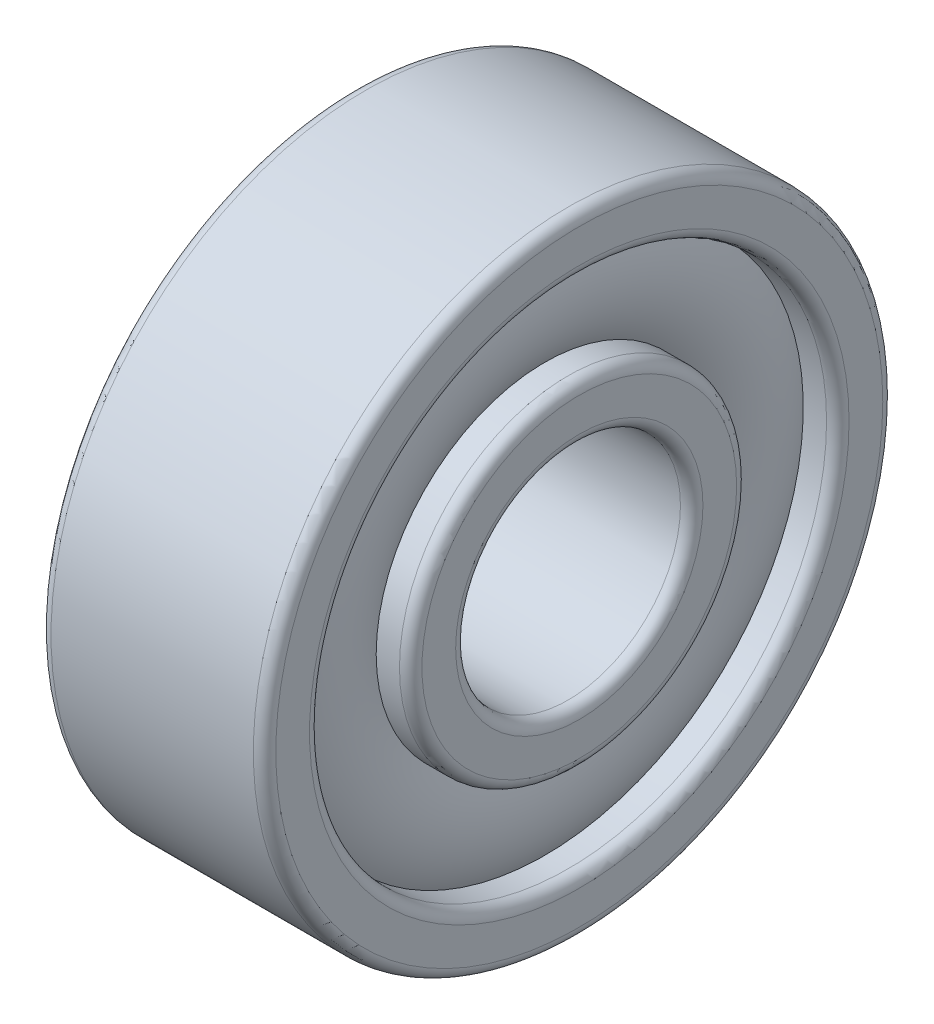
SolidWorks part; units mm, degrees
ref_plane "前视基准面" through (0, 0, 0) normal (0, 0, 1) x (1, 0, 0)
ref_plane "上视基准面" through (0, 0, 0) normal (0, 1, 0) x (1, 0, 0)
ref_plane "右视基准面" through (0, 0, 0) normal (1, 0, 0) x (0, 0, -1)
other "Configuration Table"
sketch "草图1" plane through (0, 0, 0) normal (0, 0, 1) x (1, 0, 0)
  line L0 (-5.5784, 0) -> (6.3176, 0)
  line L2 (2.5, 2.5) -> (2.5, 3.75)
  line L3 (2.5, 7) -> (-2.5, 7)
  line L4 (-2.5, 2.5) -> (-2.5, 3.75)
  line L5 (2.5, 2.5) -> (-2.5, 7) construction
  line L6 (2.5, 7) -> (-2.5, 2.5) construction
  line L7 (-2.5, 2.5) -> (-2.5, 0)
  line L8 (2.5, 2.5) -> (2.5, 0)
  line L9 (-2.5, 0) -> (2.5, 0)
  line L10 (-2.5, 7) -> (-2.5, 5.75)
  line L11 (2.5, 7) -> (2.5, 5.75)
  line L12 (2.5, 5.75) -> (1.7321, 5.75)
  line L13 (2.5, 5.75) -> (2.5, 7)
  line L14 (-2.5, 3.75) -> (-1.7321, 3.75)
  line L15 (-1.7321, 5.75) -> (-2.5, 5.75)
  line L16 (1.7321, 3.75) -> (2.5, 3.75)
  line L18 (-2.5, 5.75) -> (-2.5, 7)
  arc A0 (-1.7321, 5.75) -> (-1.7321, 3.75) centre (0, 4.75) ccw
  arc A1 (1.7321, 3.75) -> (1.7321, 5.75) centre (0, 4.75) ccw
  point P0 (0, 4.75)
  dimension "D6" = 4
  dimension "D1" = 4.5
  dimension "D2" = 5
  dimension "D3" = 0
  dimension "D4" = 1.25
  dimension "D5" = 1.25
  dimension "D7" = 2
  dimension "D8" = 2
  dimension "D9" = 2.5
revolve "旋转1" add sketch "草图1" angle 360 about L0
sketch "草图2" plane through (-2.5, 0, 0) normal (-1, 0, 0) x (0, 0, 1)
  circle A0 centre (0, 0) radius 2.5
  dimension "D1" = 5
extrude "切除-拉伸1" cut sketch "草图2" against normal blind 5
fillet "圆角1" radius 0.25 8 edges at (2.5, 0, 3.75) (-2.5, 0, 3.75) (-2.5, 0, 5.75) (-2.5, 0, 7) (2.5, 0, 7) (2.5, 0, 5.75) (2.5, 0, 2.5) (-2.5, 0, 2.5)
